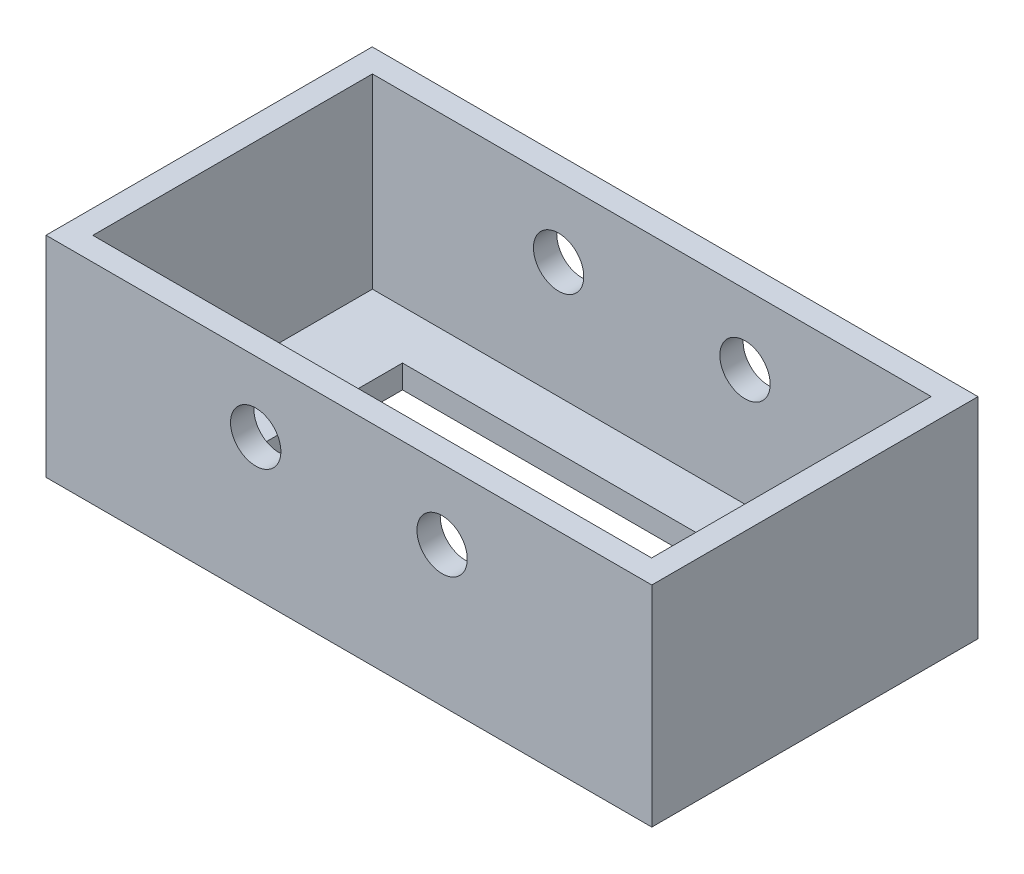
SolidWorks part; units mm, degrees
ref_plane "Front Plane" through (0, 0, 0) normal (0, 0, 1) x (1, 0, 0)
ref_plane "Top Plane" through (0, 0, 0) normal (0, 1, 0) x (1, 0, 0)
ref_plane "Right Plane" through (0, 0, 0) normal (1, 0, 0) x (0, 0, -1)
sketch "Sketch1" plane through (0, 0, 0) normal (0, 1, 0) x (1, 0, 0)
  line L1 (0, 0) -> (82.55, 0)
  line L2 (0, 0) -> (0, 44.45)
  line L3 (0, 44.45) -> (82.55, 44.45)
  line L4 (82.55, 0) -> (82.55, 44.45)
  dimension "D1" = 82.55
  dimension "D2" = 44.45
extrude "Boss-Extrude1" add sketch "Sketch1" along normal blind 3.175
sketch "Sketch2" plane through (0, 3.175, 0) normal (0, 1, 0) x (1, 0, 0)
  line L0 (0, 44.45) -> (0, 0) construction
  line L1 (82.55, 44.45) -> (0, 44.45) construction
  line L2 (41.275, 44.45) -> (41.275, 0) construction
  line L3 (0, 0) -> (82.55, 0) construction
  circle A0 centre (9.525, 22.225) radius 2.54
  circle A1 centre (73.025, 22.225) radius 2.54
  dimension "D2" = 5.08
  dimension "D3" = 22.225
  dimension "D1" = 9.525
extrude "Cut-Extrude1" cut sketch "Sketch2" against normal blind 3.175
sketch "Sketch4" plane through (0, 3.175, 0) normal (0, 1, 0) x (1, 0, 0)
  line L0 (0, 44.45) -> (0, 0) construction
  line L1 (13.97, 34.6075) -> (68.58, 34.6075)
  line L2 (13.97, 34.6075) -> (13.97, 9.8425)
  line L3 (13.97, 9.8425) -> (68.58, 9.8425)
  line L4 (68.58, 34.6075) -> (68.58, 9.8425)
  line L5 (82.55, 0) -> (82.55, 44.45) construction
  line L6 (82.55, 44.45) -> (0, 44.45) construction
  line L7 (0, 0) -> (82.55, 0) construction
  dimension "D1" = 13.97
  dimension "D2" = 13.97
  dimension "D3" = 9.8425
  dimension "D4" = 9.8425
extrude "Cut-Extrude2" cut sketch "Sketch4" against normal blind 3.175
sketch "Sketch5" plane through (0, 3.175, 0) normal (0, 1, 0) x (1, 0, 0)
  line L0 (82.55, 44.45) -> (0, 44.45) construction
  line L1 (0, 44.45) -> (82.55, 44.45)
  line L2 (0, 44.45) -> (0, 41.275)
  line L3 (0, 41.275) -> (82.55, 41.275)
  line L4 (82.55, 44.45) -> (82.55, 41.275)
  line L5 (0, 44.45) -> (0, 0) construction
  line L6 (0, 22.225) -> (82.55, 22.225) construction
  line L7 (82.55, 0) -> (82.55, 44.45) construction
  line L8 (0, 3.175) -> (82.55, 3.175)
  line L9 (82.55, 0) -> (82.55, 3.175)
  line L10 (0, 0) -> (82.55, 0)
  line L11 (0, 0) -> (0, 3.175)
  dimension "D1" = 82.55
  dimension "D3" = 3.175
extrude "Boss-Extrude2" add sketch "Sketch5" along normal blind 25.4
sketch "Sketch6" plane through (0, 0, -44.45) normal (0, 0, -1) x (-1, 0, 0)
  line L2 (-82.55, 28.575) -> (0, 28.575) construction
  circle A0 centre (-28.575, 19.05) radius 3.429
  circle A1 centre (-53.975, 19.05) radius 3.429
  point P2 (0, 0)
  point P5 (-41.275, 28.575)
  dimension "D2" = 12.7
  dimension "D3" = 6.858
  dimension "D1" = 9.525
  dimension "D4" = 25.4
sketch "Sketch7" plane through (0, 3.175, 0) normal (0, 1, 0) x (1, 0, 0)
  line L0 (82.55, 3.175) -> (0, 3.175) construction
  line L1 (0, 41.275) -> (3.2043, 41.275)
  line L2 (0, 41.275) -> (0, 3.175)
  line L3 (0, 3.175) -> (3.2043, 3.175)
  line L4 (3.2043, 41.275) -> (3.2043, 3.175)
  line L5 (41.275, 41.275) -> (41.275, 3.175) construction
  line L6 (0, 41.275) -> (82.55, 41.275) construction
  line L7 (82.55, 3.175) -> (79.3457, 3.175)
  line L8 (79.3457, 41.275) -> (79.3457, 3.175)
  line L9 (82.55, 41.275) -> (79.3457, 41.275)
  line L10 (82.55, 41.275) -> (82.55, 3.175)
extrude "Boss-Extrude3" add sketch "Sketch7" along normal blind 25.4
extrude "Cut-Extrude3" cut sketch "Sketch6" against normal through all
